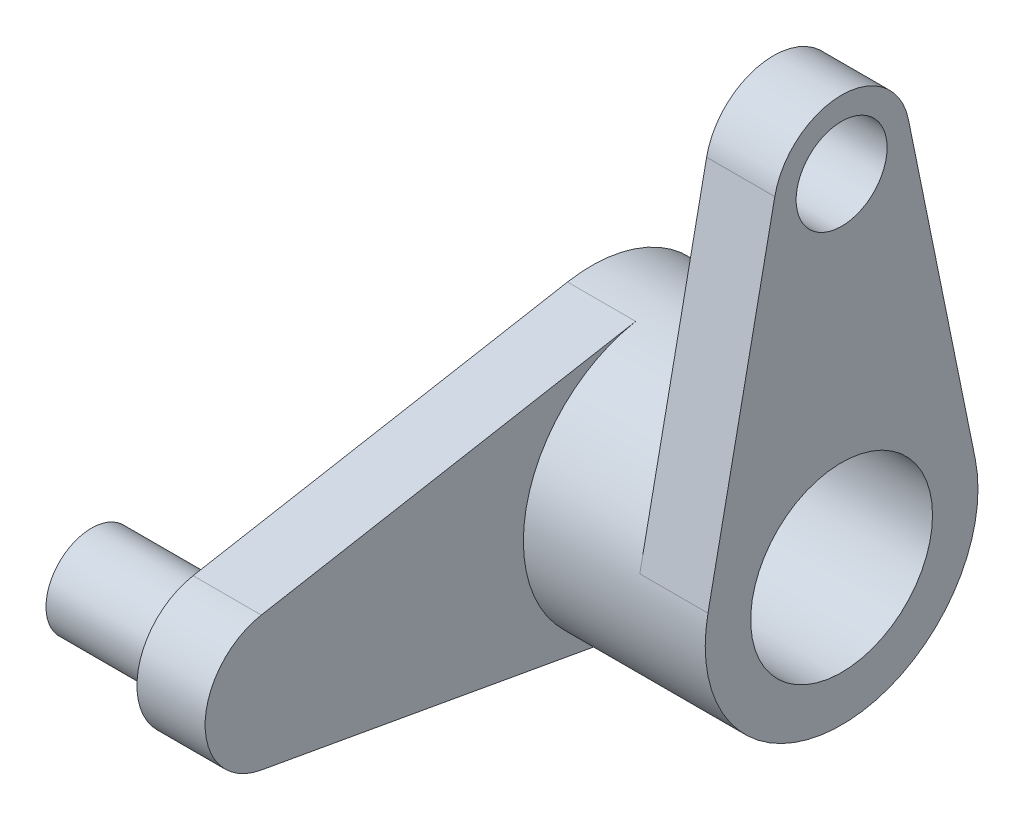
SolidWorks part; units mm, degrees
ref_plane "Front Plane" through (0, 0, 0) normal (1, 0, 0) x (0, 1, 0)
ref_plane "Top Plane" through (0, 0, 0) normal (0, 0, 1) x (0, 1, 0)
ref_plane "Right Plane" through (0, 0, 0) normal (0, 1, 0) x (-1, 0, 0)
sketch "Sketch1" plane through (0, 0, 0) normal (1, 0, 0) x (0, 1, 0)
  line L0 (-14.7646, 87.6471) -> (-29.5292, 5.2941)
  line L1 (0, 0) -> (0, 14.8287) construction
  line L2 (14.7646, 87.6471) -> (29.5292, 5.2941)
  arc A1 (-29.5292, 5.2941) -> (29.5292, 5.2941) centre (0, 0) ccw
  arc A2 (14.7646, 87.6471) -> (-14.7646, 87.6471) centre (0, 85) ccw
  dimension "D1" = 60
  dimension "D3" = 30
  dimension "D4" = 85
extrude "Boss-Extrude1" add sketch "Sketch1" along normal blind 15
sketch "Sketch2" plane through (15, 0, 0) normal (1, 0, 0) x (0, 1, 0)
  circle A0 centre (0, 0) radius 30
extrude "Boss-Extrude2" add sketch "Sketch2" along normal blind 25
sketch "Sketch3" plane through (40, 0, 0) normal (1, 0, 0) x (0, 1, 0)
  line L0 (6, 29.3939) -> (78, 14.6969)
  line L1 (0, 0) -> (15.8836, 0) construction
  line L2 (6, -29.3939) -> (78, -14.6969)
  arc A0 (6, 29.3939) -> (6, -29.3939) centre (0, 0) ccw
  circle A1 centre (0, 0) radius 20
  circle A2 centre (75, 0) radius 10
  arc A3 (78, -14.6969) -> (78, 14.6969) centre (75, 0) ccw
  dimension "D1" = 60
  dimension "D2" = 40
  dimension "D3" = 20
  dimension "D4" = 30
  dimension "D5" = 75
extrude "Boss-Extrude3" add sketch "Sketch3" along normal blind 15
sketch "Sketch4" plane through (55, 0, 0) normal (1, 0, 0) x (0, 1, 0)
  circle A0 centre (0, 0) radius 20
extrude "Cut-Extrude1" cut sketch "Sketch4" against normal through all both and the other way through all
sketch "Sketch5" plane through (0, 0, 0) normal (-1, 0, 0) x (0, -1, 0)
  circle A0 centre (0, 85) radius 10
  dimension "D1" = 20
extrude "Boss-Extrude4" add sketch "Sketch5" along normal blind 25
